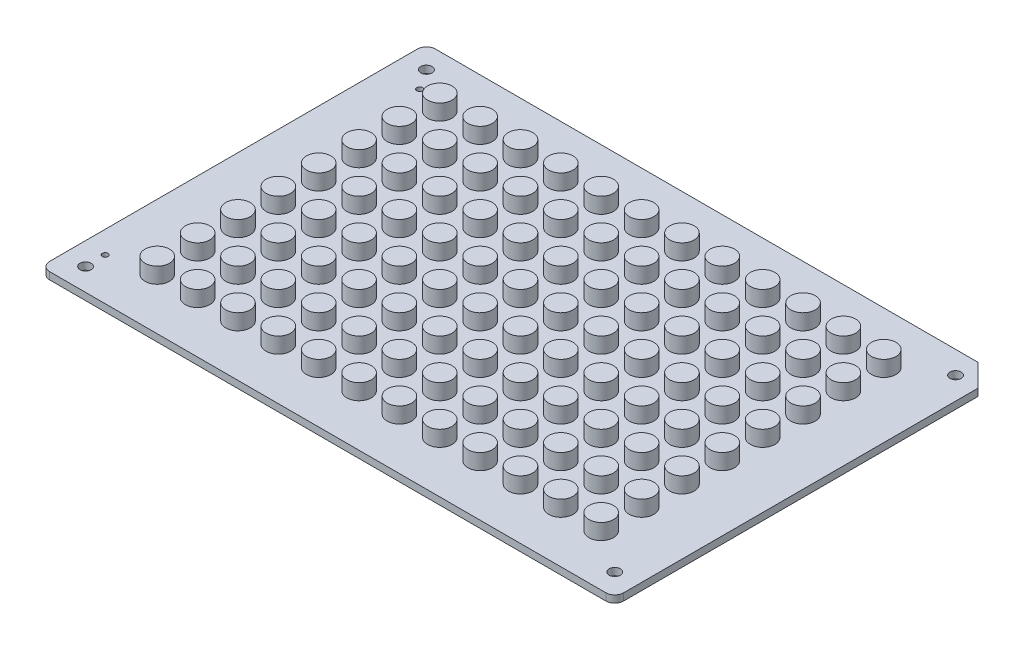
SolidWorks part; units mm, degrees
ref_plane "Front Plane" through (0, 0, 0) normal (0, 0, 1) x (1, 0, 0)
ref_plane "Top Plane" through (0, 0, 0) normal (0, 1, 0) x (1, 0, 0)
ref_plane "Right Plane" through (0, 0, 0) normal (1, 0, 0) x (0, 0, -1)
sketch "Sketch1" plane through (0, 0, 0) normal (0, 1, 0) x (1, 0, 0)
  line L0 (-43.0325, 69.6847) -> (-43.0325, -12.3153)
  line L1 (-41.0325, -14.3153) -> (82.9675, -14.3153)
  line L2 (84.9675, -12.3153) -> (84.9675, 66.6847)
  line L3 (84.9675, 66.6847) -> (79.9675, 71.6847)
  line L4 (79.9675, 71.6847) -> (-41.0325, 71.6847)
  circle A0 centre (-38.0325, 66.6847) radius 1.25
  circle A1 centre (-38.0325, -9.3153) radius 1.25
  circle A2 centre (79.9675, -9.3153) radius 1.25
  circle A3 centre (79.9675, 66.6847) radius 1.25
  circle A4 centre (-38.0795, -4.9061) radius 0.635
  circle A5 centre (-35.0295, 62.1739) radius 0.635
  arc A6 (-41.0325, 71.6847) -> (-43.0325, 69.6847) centre (-41.0325, 69.6847) ccw
  arc A7 (-43.0325, -12.3153) -> (-41.0325, -14.3153) centre (-41.0325, -12.3153) ccw
  arc A8 (82.9675, -14.3153) -> (84.9675, -12.3153) centre (82.9675, -12.3153) ccw
extrude "Boss-Extrude1" add sketch "Sketch1" along normal blind 1.6
sketch "Sketch2" plane through (0, 1.6, 0) normal (0, 1, 0) x (1, 0, 0)
  line L0 (79.9675, 71.6847) -> (-41.0325, 71.6847) construction
  line L2 (-43.0325, 69.6847) -> (-43.0325, -12.3153) construction
  circle A0 centre (-28.5325, 60.1697) radius 2.73
  circle A96 centre (-19.5325, 60.1697) radius 2.73
  circle A97 centre (-10.5325, 60.1697) radius 2.73
  circle A98 centre (-1.5325, 60.1697) radius 2.73
  circle A99 centre (7.4675, 60.1697) radius 2.73
  circle A100 centre (16.4675, 60.1697) radius 2.73
  circle A101 centre (25.4675, 60.1697) radius 2.73
  circle A102 centre (34.4675, 60.1697) radius 2.73
  circle A103 centre (43.4675, 60.1697) radius 2.73
  circle A104 centre (52.4675, 60.1697) radius 2.73
  circle A105 centre (61.4675, 60.1697) radius 2.73
  circle A106 centre (70.4675, 60.1697) radius 2.73
  circle A107 centre (-19.5325, 51.1697) radius 2.73
  circle A108 centre (-10.5325, 51.1697) radius 2.73
  circle A109 centre (-1.5325, 51.1697) radius 2.73
  circle A110 centre (7.4675, 51.1697) radius 2.73
  circle A111 centre (16.4675, 51.1697) radius 2.73
  circle A112 centre (25.4675, 51.1697) radius 2.73
  circle A113 centre (34.4675, 51.1697) radius 2.73
  circle A114 centre (43.4675, 51.1697) radius 2.73
  circle A115 centre (52.4675, 51.1697) radius 2.73
  circle A116 centre (61.4675, 51.1697) radius 2.73
  circle A117 centre (70.4675, 51.1697) radius 2.73
  circle A118 centre (-19.5325, 42.1697) radius 2.73
  circle A119 centre (-10.5325, 42.1697) radius 2.73
  circle A120 centre (-1.5325, 42.1697) radius 2.73
  circle A121 centre (7.4675, 42.1697) radius 2.73
  circle A122 centre (16.4675, 42.1697) radius 2.73
  circle A123 centre (25.4675, 42.1697) radius 2.73
  circle A124 centre (34.4675, 42.1697) radius 2.73
  circle A125 centre (43.4675, 42.1697) radius 2.73
  circle A126 centre (52.4675, 42.1697) radius 2.73
  circle A127 centre (61.4675, 42.1697) radius 2.73
  circle A128 centre (70.4675, 42.1697) radius 2.73
  circle A129 centre (-19.5325, 33.1697) radius 2.73
  circle A130 centre (-10.5325, 33.1697) radius 2.73
  circle A131 centre (-1.5325, 33.1697) radius 2.73
  circle A132 centre (7.4675, 33.1697) radius 2.73
  circle A133 centre (16.4675, 33.1697) radius 2.73
  circle A134 centre (25.4675, 33.1697) radius 2.73
  circle A135 centre (34.4675, 33.1697) radius 2.73
  circle A136 centre (43.4675, 33.1697) radius 2.73
  circle A137 centre (52.4675, 33.1697) radius 2.73
  circle A138 centre (61.4675, 33.1697) radius 2.73
  circle A139 centre (70.4675, 33.1697) radius 2.73
  circle A140 centre (-19.5325, 24.1697) radius 2.73
  circle A141 centre (-10.5325, 24.1697) radius 2.73
  circle A142 centre (-1.5325, 24.1697) radius 2.73
  circle A143 centre (7.4675, 24.1697) radius 2.73
  circle A144 centre (16.4675, 24.1697) radius 2.73
  circle A145 centre (25.4675, 24.1697) radius 2.73
  circle A146 centre (34.4675, 24.1697) radius 2.73
  circle A147 centre (43.4675, 24.1697) radius 2.73
  circle A148 centre (52.4675, 24.1697) radius 2.73
  circle A149 centre (61.4675, 24.1697) radius 2.73
  circle A150 centre (70.4675, 24.1697) radius 2.73
  circle A151 centre (-19.5325, 15.1697) radius 2.73
  circle A152 centre (-10.5325, 15.1697) radius 2.73
  circle A153 centre (-1.5325, 15.1697) radius 2.73
  circle A154 centre (7.4675, 15.1697) radius 2.73
  circle A155 centre (16.4675, 15.1697) radius 2.73
  circle A156 centre (25.4675, 15.1697) radius 2.73
  circle A157 centre (34.4675, 15.1697) radius 2.73
  circle A158 centre (43.4675, 15.1697) radius 2.73
  circle A159 centre (52.4675, 15.1697) radius 2.73
  circle A160 centre (61.4675, 15.1697) radius 2.73
  circle A161 centre (70.4675, 15.1697) radius 2.73
  circle A162 centre (-19.5325, 6.1697) radius 2.73
  circle A163 centre (-10.5325, 6.1697) radius 2.73
  circle A164 centre (-1.5325, 6.1697) radius 2.73
  circle A165 centre (7.4675, 6.1697) radius 2.73
  circle A166 centre (16.4675, 6.1697) radius 2.73
  circle A167 centre (25.4675, 6.1697) radius 2.73
  circle A168 centre (34.4675, 6.1697) radius 2.73
  circle A169 centre (43.4675, 6.1697) radius 2.73
  circle A170 centre (52.4675, 6.1697) radius 2.73
  circle A171 centre (61.4675, 6.1697) radius 2.73
  circle A172 centre (70.4675, 6.1697) radius 2.73
  circle A173 centre (-19.5325, -2.8303) radius 2.73
  circle A174 centre (-10.5325, -2.8303) radius 2.73
  circle A175 centre (-1.5325, -2.8303) radius 2.73
  circle A176 centre (7.4675, -2.8303) radius 2.73
  circle A177 centre (16.4675, -2.8303) radius 2.73
  circle A178 centre (25.4675, -2.8303) radius 2.73
  circle A179 centre (34.4675, -2.8303) radius 2.73
  circle A180 centre (43.4675, -2.8303) radius 2.73
  circle A181 centre (52.4675, -2.8303) radius 2.73
  circle A182 centre (61.4675, -2.8303) radius 2.73
  circle A183 centre (70.4675, -2.8303) radius 2.73
  circle A184 centre (-28.5325, 51.1697) radius 2.73
  circle A185 centre (-28.5325, 42.1697) radius 2.73
  circle A186 centre (-28.5325, 33.1697) radius 2.73
  circle A187 centre (-28.5325, 24.1697) radius 2.73
  circle A188 centre (-28.5325, 15.1697) radius 2.73
  circle A189 centre (-28.5325, 6.1697) radius 2.73
  circle A190 centre (-28.5325, -2.8303) radius 2.73
  dimension "D1" = 11.515
  dimension "D5" = 5.46
  dimension "D4" = 14.5
  dimension "D2" = 12
  dimension "D3" = 8
extrude "Boss-Extrude2" add sketch "Sketch2" along normal blind 3.5
sketch "Sketch3" plane through (0, 1.6, 0) normal (0, 1, 0) x (1, 0, 0)
  line L0 (84.9675, -12.3153) -> (84.9675, 66.6847) construction
  line L1 (-41.0325, -14.3153) -> (82.9675, -14.3153) construction
  line L2 (-43.0325, 69.6847) -> (-43.0325, -12.3153) construction
  line L3 (79.9675, 71.6847) -> (-41.0325, 71.6847) construction
  line L4 (84.9675, 66.6847) -> (79.9675, 71.6847) construction
  line L5 (84.9675, -12.3153) -> (84.9675, 66.6847)
  line L6 (-41.0325, -14.3153) -> (82.9675, -14.3153)
  line L7 (-43.0325, 69.6847) -> (-43.0325, 63.68)
  line L8 (79.9675, 71.6847) -> (-41.0325, 71.6847)
  line L9 (84.9675, 66.6847) -> (79.9675, 71.6847)
  line L10 (-34.0325, 63.68) -> (73.3591, -3.9465) construction
  line L11 (-24.6567, 63.6847) -> (66.6348, 63.6847)
  line L13 (-24.7137, -6.3153) -> (67.7375, -6.3153)
  line L14 (75.9675, 57.7712) -> (75.9675, 0.3197)
  line L15 (76.524, 64.0525) -> (25.9153, 31.8385) construction
  line L16 (-34.0325, 57.7712) -> (11.9018, 28.8455)
  line L17 (66.6348, 63.6847) -> (21.2345, 34.7861)
  line L18 (-24.6567, 63.6847) -> (21.2345, 34.7861)
  line L19 (75.9675, 57.7712) -> (30.596, 28.891)
  line L20 (-31.3682, 67.911) -> (76.0234, 0.2845) construction
  line L21 (-36.6968, 59.449) -> (70.6947, -8.1775) construction
  line L22 (11.9018, 28.8455) -> (-34.0325, -0.393)
  line L23 (73.8392, 68.2705) -> (-36.7174, -2.102) construction
  line L24 (16.5825, 25.898) -> (-34.0325, -6.32) construction
  line L25 (76.524, 64.0525) -> (-34.0325, -6.32) construction
  line L26 (21.2633, 22.9504) -> (-24.7137, -6.3153)
  line L27 (79.2089, 59.8345) -> (-31.3476, -10.538) construction
  line L28 (30.596, 28.891) -> (75.9675, 0.3197)
  line L29 (21.2633, 22.9504) -> (67.7375, -6.3153)
  line L30 (-43.0325, 63.68) -> (-34.0325, 63.68)
  line L31 (-34.0325, 63.68) -> (-34.0325, 57.7712)
  line L32 (-34.0325, -0.393) -> (-34.0325, -6.32)
  line L33 (-34.0325, -6.32) -> (-43.0325, -6.32)
  line L34 (-43.0325, -6.32) -> (-43.0325, -12.3153)
  circle A0 centre (79.9675, -9.3153) radius 1.25 construction
  arc A1 (82.9675, -14.3153) -> (84.9675, -12.3153) centre (82.9675, -12.3153) ccw construction
  circle A2 centre (-38.0325, -9.3153) radius 1.25 construction
  arc A3 (-43.0325, -12.3153) -> (-41.0325, -14.3153) centre (-41.0325, -12.3153) ccw construction
  arc A4 (-41.0325, 71.6847) -> (-43.0325, 69.6847) centre (-41.0325, 69.6847) ccw construction
  circle A5 centre (79.9675, 66.6847) radius 1.25 construction
  circle A6 centre (-38.0325, 66.6847) radius 1.25 construction
  circle A7 centre (79.9675, -9.3153) radius 1.25
  arc A8 (82.9675, -14.3153) -> (84.9675, -12.3153) centre (82.9675, -12.3153) ccw
  circle A9 centre (-38.0325, -9.3153) radius 1.25
  arc A10 (-43.0325, -12.3153) -> (-41.0325, -14.3153) centre (-41.0325, -12.3153) ccw
  arc A11 (-41.0325, 71.6847) -> (-43.0325, 69.6847) centre (-41.0325, 69.6847) ccw
  circle A12 centre (79.9675, 66.6847) radius 1.25
  circle A13 centre (-38.0325, 66.6847) radius 1.25
  dimension "D1" = 8
  dimension "D2" = 70
  dimension "D3" = 9
  dimension "D4" = 8
  dimension "D7" = 9
  dimension "D5" = 5
  dimension "D6" = 5
